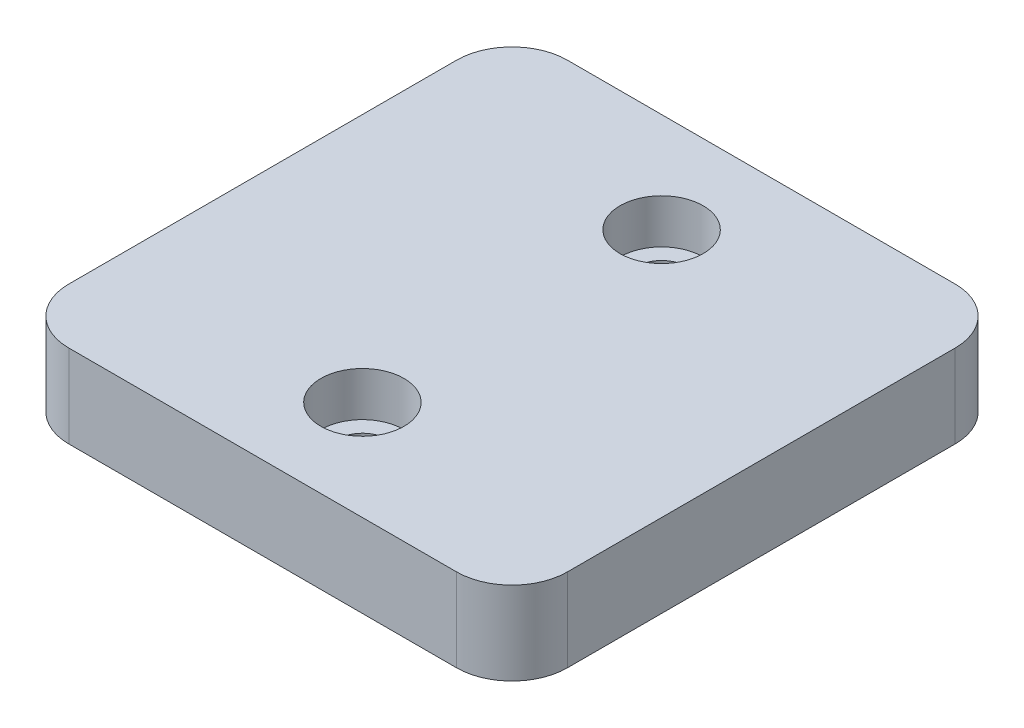
SolidWorks part; units mm, degrees
ref_plane "前视基准面" through (0, 0, 0) normal (0, 0, 1) x (1, 0, 0)
ref_plane "上视基准面" through (0, 0, 0) normal (0, 1, 0) x (1, 0, 0)
ref_plane "右视基准面" through (0, 0, 0) normal (1, 0, 0) x (0, 0, -1)
sketch "草图2" plane through (0, 0, 0) normal (0, 1, 0) x (1, 0, 0)
  line L1 (-35, 45) -> (35, 45)
  line L2 (-45, 35) -> (-45, -35)
  line L3 (-35, -45) -> (35, -45)
  line L4 (45, 35) -> (45, -35)
  line L5 (-45, 45) -> (45, -45) construction
  line L6 (-45, -45) -> (45, 45) construction
  arc A0 (35, -45) -> (45, -35) centre (35, -35) ccw
  arc A1 (-45, -35) -> (-35, -45) centre (-35, -35) ccw
  arc A2 (-35, 45) -> (-45, 35) centre (-35, 35) ccw
  arc A3 (35, 45) -> (45, 35) centre (35, 35) cw
  point P0 (0, 0)
  dimension "D3" = 10
  dimension "D1" = 90
  dimension "D2" = 90
extrude "凸台-拉伸2" add sketch "草图2" along normal blind 15
sketch "草图3" plane through (0, 15, 0) normal (0, 1, 0) x (1, 0, 0)
  line L0 (-51.8278, 0) -> (50.2587, 0) construction
  line L1 (0, 41.539) -> (0, -41.539) construction
  circle A0 centre (0, 27) radius 7.5
  circle A1 centre (0, -27) radius 7.5
  dimension "D1" = 15
  dimension "D2" = 54
extrude "切除-拉伸1" cut sketch "草图3" against normal blind 8
sketch "草图4" plane through (0, 0, 0) normal (0, -1, 0) x (1, 0, 0)
  line L0 (0, 60.1679) -> (0, -70.0588) construction
  line L1 (-69.2562, 0) -> (112.3287, 0) construction
  circle A0 centre (0, 27) radius 4.5
  circle A1 centre (0, -27) radius 4.5
  dimension "D1" = 9
  dimension "D2" = 54
extrude "切除-拉伸2" cut sketch "草图4" against normal through all
sketch "草图5" plane through (0, 15, 0) normal (0, 1, 0) x (1, 0, 0)
  line L0 (-45, 35) -> (-45, -35) construction
  line L1 (37, -8) -> (-45, -8)
  line L2 (37, -8) -> (37, 8)
  line L3 (37, 8) -> (-45, 8)
  line L4 (-45, -8) -> (-45, 8)
  line L5 (37, -8) -> (-45, 8) construction
  line L6 (37, 8) -> (-45, -8) construction
  line L7 (45, -35) -> (45, 35) construction
  point P0 (-4, 0)
  point P10 (0, 0)
  dimension "D1" = 16
  dimension "D2" = 8
ref_plane "基准面4" through (0, 0, 0) normal (0, 0, -1) x (-1, 0, 0)
sketch "扫描线" plane through (0, 0, 0) normal (0, 0, -1) x (-1, 0, 0)
  line L0 (-95, 93.3247) -> (-95, -34.0472) construction
  line L1 (-120.0762, 75) -> (-78.8672, 75) construction
  line L2 (-35, 0) -> (35, 0) construction
  line L3 (-136.0589, 15) -> (-19.1078, 15) construction
  line L4 (-37, 15) -> (45, 15) construction
  line L5 (-45, 60.1487) -> (-45, -47.0551) construction
  circle A0 centre (-95, 75) radius 17.5 construction
  arc A1 (-52.8513, 35.2345) -> (-39.9397, 15) centre (-104.5316, -11.9793) ccw construction
  arc A2 (-45, 15) -> (-52.8513, 35.2345) centre (-75, 15) ccw construction
  arc A3 (-44.8513, 35.2345) -> (-91.5508, 57.8433) centre (-96.5316, -11.9793) ccw
  arc A4 (-37, 15) -> (-44.8513, 35.2345) centre (-67, 15) ccw
  point P21 (0, 0)
  point P24 (-91.5508, 57.8433)
  point P26 (0, 0)
  point P27 (-88.4181, 58.7849)
  point P28 (0, 0)
  point P29 (0, 0)
  dimension "D3" = 35
  dimension "D4" = 140
  dimension "D5" = 60
  dimension "D7" = 2
  dimension "D1" = 95
  dimension "D2" = 75
  dimension "D6" = 45
  dimension "D8" = 8
sketch "引导线" plane through (0, 0, 0) normal (0, 0, -1) x (-1, 0, 0)
  line L0 (45, 0.0679) -> (45, 96.1428) construction
  line L1 (-95, 93.3247) -> (-95, -34.0472) construction
  circle A0 centre (-95, 75) radius 17.5 construction
  arc A1 (24.954, 24.6875) -> (45, 15.2128) centre (42.0903, 35) ccw
  arc A2 (24.954, 24.6875) -> (-95, 92.5) centre (-95, -47.5) ccw
  point P8 (45, 15)
  point P12 (45, -66.0036)
  point P13 (45, 96.1428)
  point P14 (0, 0)
  point P15 (54.5469, 35)
  point P16 (45, 17.836)
  point P17 (0, 0)
  point P18 (49.2721, 35)
  point P19 (0, 0)
  point P22 (42.0903, 35)
  point P23 (42.0903, 35)
  dimension "D1" = 35
  dimension "D3" = 40
  dimension "D5" = 280
  dimension "D2" = 45
  dimension "D4" = 35
